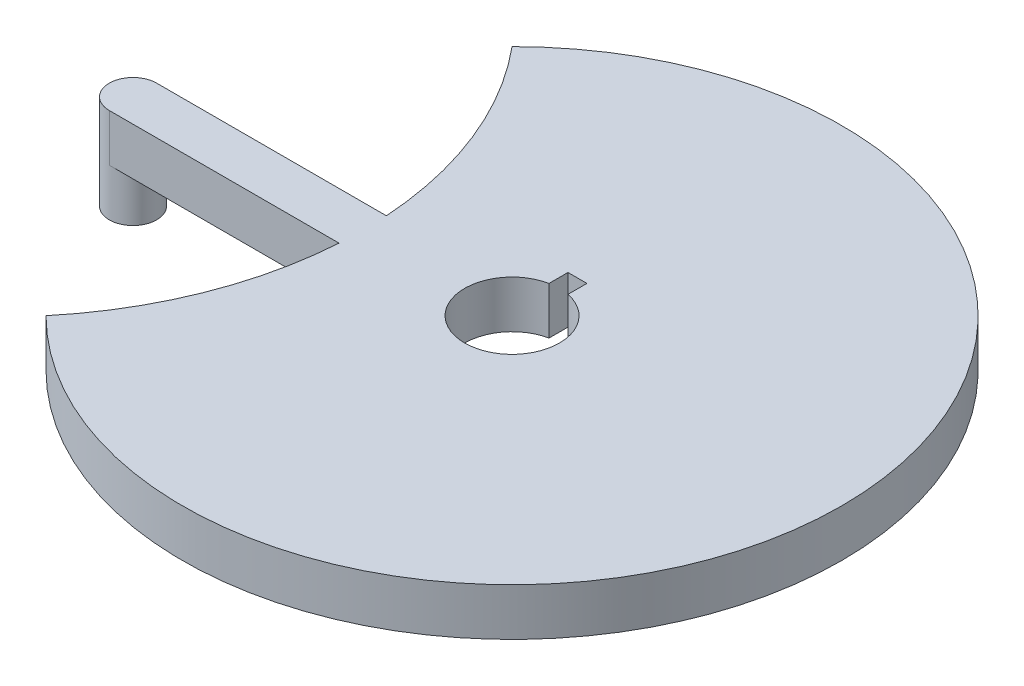
SolidWorks part; units mm, degrees
ref_plane "前视基准面" through (0, 0, 0) normal (0, 0, 1) x (1, 0, 0)
ref_plane "上视基准面" through (0, 0, 0) normal (0, 1, 0) x (1, 0, 0)
ref_plane "右视基准面" through (0, 0, 0) normal (1, 0, 0) x (0, 0, -1)
sketch "草图1" plane through (0, 0, 0) normal (0, 1, 0) x (1, 0, 0)
  line L0 (-129.4458, 0) -> (166.3539, 0) construction
  line L1 (0, 112.5965) -> (0, -118.4804) construction
  line L2 (-2, 9.798) -> (-2, 13.798)
  line L3 (-2, 13.798) -> (2, 13.798)
  line L4 (2, 9.798) -> (2, 13.798)
  line L5 (-49.1802, 49.1802) -> (0, 0) construction
  line L6 (0, 0) -> (-49.1802, -49.1802) construction
  line L8 (-80, 5) -> (-31.5207, 5)
  line L9 (-80, -5) -> (-31.5207, -5)
  arc A0 (-49.1802, -49.1802) -> (-49.1802, 49.1802) centre (0, 0) ccw
  arc A1 (-2, 9.798) -> (2, 9.798) centre (0, 0) ccw
  arc A2 (-49.1802, -49.1802) -> (-31.5207, -5) centre (-108.1238, 0) ccw
  arc A3 (-80, 5) -> (-80, -5) centre (-80, 0) ccw
  arc A4 (-31.5207, 5) -> (-49.1802, 49.1802) centre (-108.1238, 0) ccw
  point P13 (0, 13.798)
  dimension "D1" = 4
  dimension "D2" = 90
  dimension "D3" = 10
  dimension "D5" = 10
  dimension "D4" = 4
  dimension "D6" = 80
extrude "凸台-拉伸1" add sketch "草图1" along normal blind 10
sketch "草图2" plane through (0, 0, 0) normal (0, -1, 0) x (1, 0, 0)
  circle A0 centre (-80, 0) radius 5
  dimension "D1" = 80
extrude "凸台-拉伸2" add sketch "草图2" along normal blind 10
